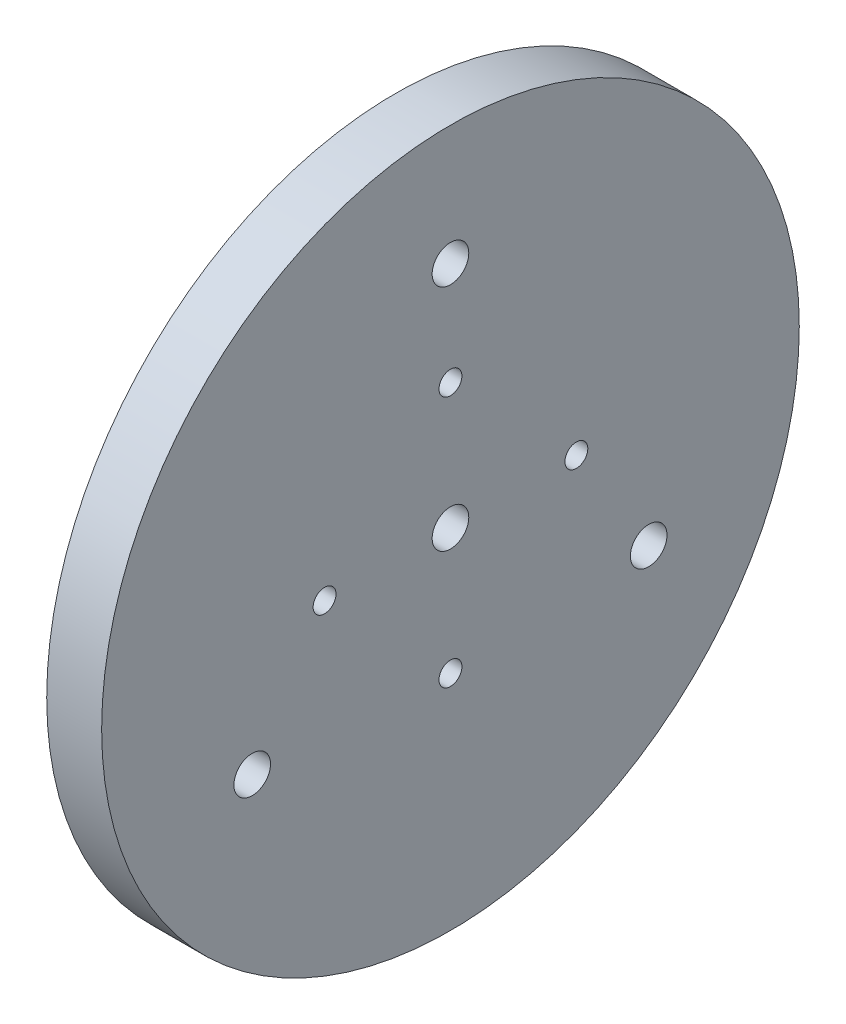
SolidWorks part; units mm, degrees
ref_plane "Front Plane" through (0, 0, 0) normal (0, 0, 1) x (1, 0, 0)
ref_plane "Top Plane" through (0, 0, 0) normal (0, 1, 0) x (1, 0, 0)
ref_plane "Right Plane" through (0, 0, 0) normal (1, 0, 0) x (0, 0, -1)
sketch "Sketch2" plane through (0, 0, 0) normal (1, 0, 0) x (0, 0, -1)
  line L0 (0, 76.2) -> (0, -76.2) construction
  line L1 (-76.2, 0) -> (79.9536, 0) construction
  circle A0 centre (0, 0) radius 76.2
  circle A1 centre (0, 27.5) radius 2.5
  circle A2 centre (27.5, 0) radius 2.5
  circle A3 centre (0, -27.5) radius 2.5
  circle A4 centre (-27.5, 0) radius 2.5
  circle A5 centre (0, 50) radius 4
  circle A6 centre (43.3013, -25) radius 4
  circle A7 centre (-43.3013, -25) radius 4
  circle A8 centre (0, 0) radius 4
  circle A9 centre (0, 0) radius 22.5 construction
  point P18 (0, 0)
  point P24 (0, 0)
  dimension "D1" = 152.4
  dimension "D2" = 5
  dimension "D4" = 55
  dimension "D5" = 8
  dimension "D6" = 50
  dimension "D8" = 8
  dimension "D9" = 45
  dimension "D3" = 4
  dimension "D7" = 3
extrude "Boss-Extrude1" add sketch "Sketch2" along normal blind 12
